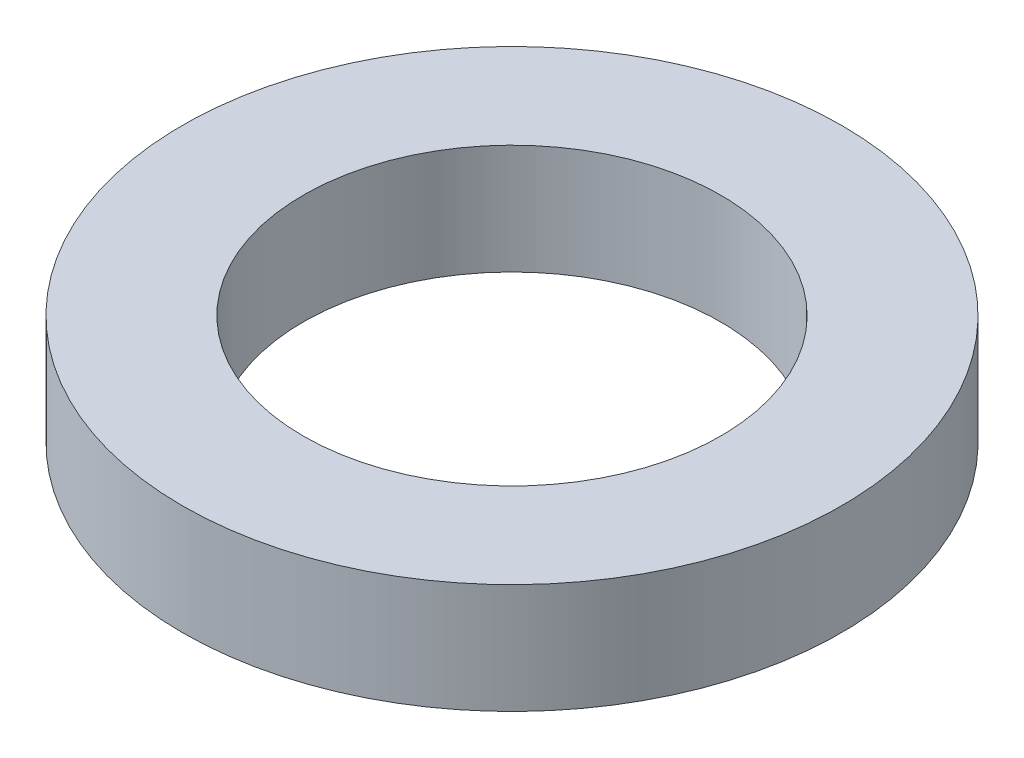
SolidWorks part; units mm, degrees
ref_plane "Front Plane" through (0, 0, 0) normal (0, 0, 1) x (1, 0, 0)
ref_plane "Top Plane" through (0, 0, 0) normal (0, 1, 0) x (1, 0, 0)
ref_plane "Right Plane" through (0, 0, 0) normal (1, 0, 0) x (0, 0, -1)
sketch "Sketch2" plane through (0, 0, 0) normal (0, 1, 0) x (1, 0, 0)
  circle A0 centre (0, 0) radius 1.9
  circle A1 centre (0, 0) radius 3
  dimension "D1" = 3.8
  dimension "D2" = 6
extrude "Boss-Extrude1" add sketch "Sketch2" along normal blind 1
